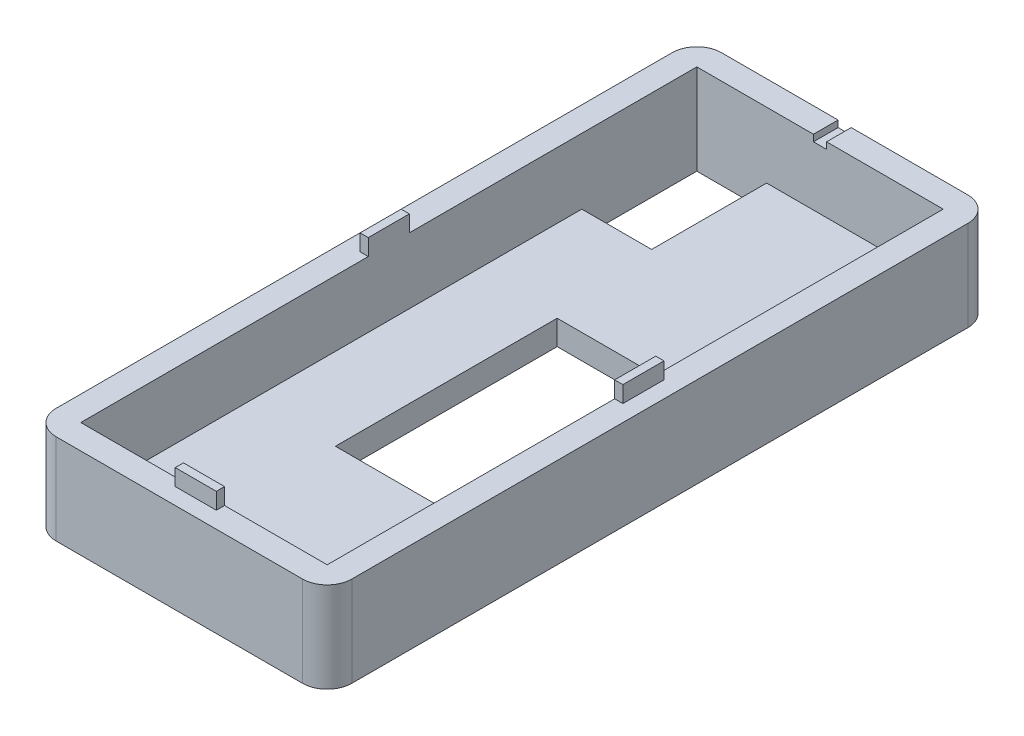
SolidWorks part; units mm, degrees
ref_plane "Front Plane" through (0, 0, 0) normal (0, 0, 1) x (1, 0, 0)
ref_plane "Top Plane" through (0, 0, 0) normal (0, 1, 0) x (1, 0, 0)
ref_plane "Right Plane" through (0, 0, 0) normal (1, 0, 0) x (0, 0, -1)
sketch "Sketch1" plane through (0, 0, 0) normal (0, 1, 0) x (1, 0, 0)
  line L1 (0, 0) -> (36, 0)
  line L2 (0, 0) -> (0, 81)
  line L3 (0, 81) -> (36, 81)
  line L4 (36, 0) -> (36, 81)
  dimension "D1" = 36
  dimension "D2" = 81
extrude "Boss-Extrude1" add sketch "Sketch1" along normal blind 11
sketch "Sketch2" plane through (0, 11, 0) normal (0, 1, 0) x (1, 0, 0)
  line L0 (36, 81) -> (0, 81) construction
  line L1 (3, 3) -> (33, 3)
  line L2 (3, 3) -> (3, 78)
  line L3 (3, 78) -> (33, 78)
  line L4 (33, 3) -> (33, 78)
  line L5 (0, 0) -> (36, 0) construction
  line L6 (0, 81) -> (0, 0) construction
  line L7 (36, 0) -> (36, 81) construction
  dimension "D1" = 3
  dimension "D2" = 3
  dimension "D3" = 3
  dimension "D4" = 3
extrude "Cut-Extrude1" cut sketch "Sketch2" against normal blind 8
fillet "Fillet1" radius 3 4 edges at (0, 5.5, 0) (36, 5.5, 0) (36, 5.5, -81) (0, 5.5, -81)
sketch "Sketch3" plane through (0, 11, 0) normal (0, 1, 0) x (1, 0, 0)
  line L0 (18, 81) -> (18, 78) construction
  line L1 (33, 81) -> (3, 81) construction
  line L2 (33, 78) -> (3, 78) construction
  line L3 (33, 78) -> (3, 78) construction
  line L4 (17.2, 81) -> (18.8, 81)
  line L5 (17.2, 81) -> (17.2, 78)
  line L6 (17.2, 78) -> (18.8, 78)
  line L7 (18.8, 81) -> (18.8, 78)
  point P14 (12.6103, 78.9326)
  dimension "D1" = 0.8
  dimension "D2" = 0.8
extrude "Cut-Extrude2" cut sketch "Sketch3" against normal blind 0.8
sketch "Sketch4" plane through (0, 11, 0) normal (0, 1, 0) x (1, 0, 0)
  line L0 (3, 78) -> (3, 3) construction
  line L1 (3, 43) -> (2, 43)
  line L2 (3, 43) -> (3, 38)
  line L3 (3, 38) -> (2, 38)
  line L4 (2, 43) -> (2, 38)
  line L5 (0, 40.5) -> (3, 40.5) construction
  line L6 (0, 78) -> (0, 3) construction
  line L7 (3, 78) -> (3, 3) construction
  line L8 (2, 40.5) -> (3, 40.5) construction
  line L9 (33, 40.5) -> (36, 40.5) construction
  line L10 (33, 3) -> (33, 78) construction
  line L11 (36, 3) -> (36, 78) construction
  line L12 (33, 40.5) -> (34, 40.5) construction
  line L13 (33, 43) -> (34, 43)
  line L14 (33, 43) -> (33, 38)
  line L15 (33, 38) -> (34, 38)
  line L16 (34, 43) -> (34, 38)
  line L17 (18, 3) -> (18, 0) construction
  line L18 (3, 3) -> (33, 3) construction
  line L19 (3, 0) -> (33, 0) construction
  line L20 (18, 3) -> (18, 2) construction
  line L21 (15.5, 3) -> (20.5, 3)
  line L22 (15.5, 3) -> (15.5, 2)
  line L23 (15.5, 2) -> (20.5, 2)
  line L24 (20.5, 3) -> (20.5, 2)
  dimension "D1" = 1
  dimension "D2" = 5
  dimension "D3" = 1
  dimension "D4" = 5
  dimension "D5" = 1
  dimension "D6" = 5
extrude "Boss-Extrude2" add sketch "Sketch4" along normal blind 2
sketch "Sketch5" plane through (0, 0, 0) normal (0, -1, 0) x (1, 0, 0)
  line L0 (33, 0) -> (33, -81) construction
  line L1 (36, -3) -> (0, -3) construction
  line L2 (0, -78) -> (36, -78) construction
  line L7 (3, -81) -> (3, 0) construction
  line L9 (3, -78) -> (11.5, -78)
  line L10 (3, -78) -> (3, -64)
  line L11 (3, -64) -> (11.5, -64)
  line L12 (11.5, -78) -> (11.5, -64)
  line L13 (28, -51) -> (13, -51)
  line L14 (28, -51) -> (28, -24)
  line L15 (28, -24) -> (13, -24)
  line L16 (13, -51) -> (13, -24)
  dimension "D1" = 14
  dimension "D2" = 8.5
  dimension "D3" = 5
  dimension "D4" = 27
  dimension "D5" = 21
  dimension "D6" = 15
extrude "Cut-Extrude4" cut sketch "Sketch5" against normal blind 8
